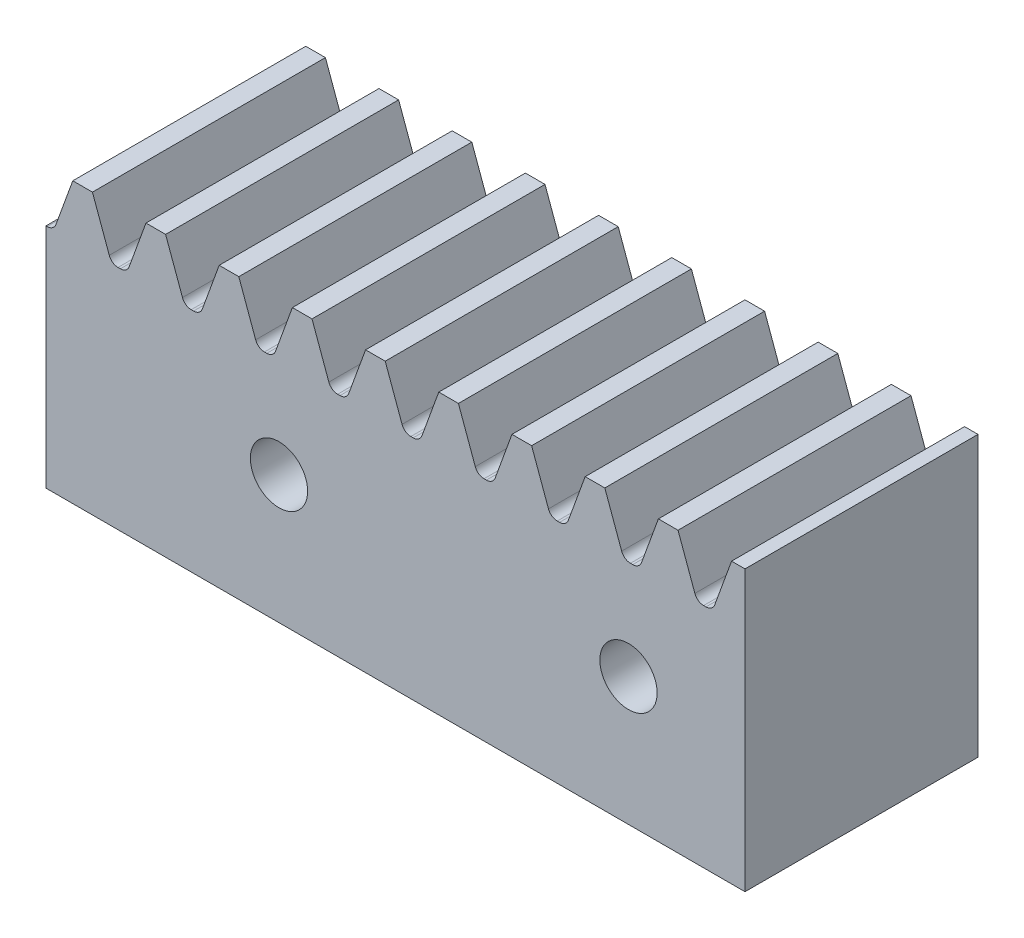
SolidWorks part; units mm, degrees
ref_plane "Front Plane" through (0, 0, 0) normal (0, 0, 1) x (1, 0, 0)
ref_plane "Top Plane" through (0, 0, 0) normal (0, 1, 0) x (1, 0, 0)
ref_plane "Right Plane" through (0, 0, 0) normal (1, 0, 0) x (0, 0, -1)
ref_plane "Dim.Module" through (1, 0, 0) normal (1, 0, 0) x (0, 0, -1)
sketch "Sketch1" plane through (0, 0, 0) normal (0, 0, 1) x (1, 0, 0)
  line L1 (0, 0) -> (30, 0)
  line L2 (0, 0) -> (0, 12)
  line L3 (0, 12) -> (30, 12)
  line L4 (30, 0) -> (30, 12)
  dimension "H" = 12
  dimension "L" = 30
extrude "Boss-Extrude1" add sketch "Sketch1" against normal mid plane 10
sketch "Sketch2" plane through (0, 0, 5) normal (0, 0, 1) x (1, 0, 0)
  line L0 (0, 0) -> (0, 12) construction
  line L2 (-1.1494, 12) -> (1.1494, 12)
  line L3 (1.1494, 12) -> (0.4262, 10.0132)
  line L4 (0.0504, 9.75) -> (-0.0504, 9.75)
  line L5 (30, 0) -> (30, 12) construction
  line L6 (-0.7854, 11) -> (30, 11) construction
  line L9 (-1.1494, 12) -> (-0.4262, 10.0132)
  line L10 (0, 12) -> (0, 0) construction
  line L11 (30, 12) -> (0, 12) construction
  arc A0 (0.4262, 10.0132) -> (0.0504, 9.75) centre (0.0504, 10.15) cw
  arc A1 (-0.4262, 10.0132) -> (-0.0504, 9.75) centre (-0.0504, 10.15) ccw
  dimension "D2" = 20
  dimension "H_s" = 11
  dimension "KSS_3" = 0.4
extrude "Cut-Extrude1" cut sketch "Sketch2" against normal through all
pattern_linear "LPattern1" count 10 spacing 3.1416 along (1, 0, 0) of "Cut-Extrude1"
hole_wizard "Tap1" positions "Sketch4" profile "Sketch3" hole size "M3x0.5" standard "JIS"
sketch "Sketch4" plane through (-45.4166, 4.6308, 5) normal (0, 0, -1) x (-1, 0, 0)
  line L0 (-45.4166, 0.8692) -> (-75.4166, 0.8692) construction
  line L4 (-45.4166, -4.6308) -> (-75.4166, -4.6308) construction
  line L7 (-45.4166, -4.6308) -> (-45.4166, 7.3692) construction
  line L8 (-75.4166, -4.6308) -> (-75.4166, 7.3692) construction
  point P0 (-55.4166, 0.8692)
  dimension "A" = 10
  dimension "H_s/2" = 5.5
sketch "Sketch3" plane through (10, 5.5, 5) normal (1, 0, 0) x (0, -1, 0)
  line L0 (0, 0) -> (0, 6.7388)
  line L1 (0, 6.7388) -> (1.2295, 6)
  line L2 (1.2295, 6) -> (1.2295, 0)
  line L5 (1.2295, 0) -> (0, 0)
  line L10 (0, 6.7388) -> (-1.2295, 6) construction
  line L11 (0, 0) -> (0, 6.7388) construction
  dimension "Drill Angle" = 118
  dimension "HSL_1" = 6
cosmetic thread "Thread1"
hole_wizard "Tap2" [suppressed] positions "Sketch6" profile "Sketch5" hole size "M3x0.5" standard "JIS"
sketch "Sketch6" [suppressed] plane through (-24.5925, 4.8567, 5) normal (0, 0, -1) x (-1, 0, 0)
  line L1 (-174.5925, 0.6433) -> (-24.5925, 0.6433) construction
  line L6 (-24.5925, -4.8567) -> (-24.5925, 7.1433) construction
  line L7 (-174.5925, -4.8567) -> (-174.5925, 7.1433) construction
  line L8 (-24.5925, -4.8567) -> (-174.5925, -4.8567) construction
  point P0 (-69.5925, 0.6433)
  dimension "F" = 0
  dimension "H_s/2" = 5.5
sketch "Sketch5" [suppressed] plane through (45, 5.5, 5) normal (1, 0, 0) x (0, -1, 0)
  line L0 (0, 0) -> (0, 6.7388)
  line L1 (0, 6.7388) -> (1.2295, 6)
  line L2 (1.2295, 6) -> (1.2295, 0)
  line L5 (1.2295, 0) -> (0, 0)
  line L10 (0, 6.7388) -> (-1.2295, 6) construction
  line L11 (0, 0) -> (0, 6.7388) construction
  dimension "Drill Angle" = 118
  dimension "HSL_1" = 6
cosmetic thread "Thread2" [suppressed]
pattern_linear "LPattern2" [suppressed]
hole_wizard "Tap3" positions "Sketch8" profile "Sketch7" hole size "M3x0.5" standard "JIS"
sketch "Sketch8" plane through (-24.7922, 5.7087, 5) normal (0, 0, -1) x (-1, 0, 0)
  line L0 (-24.7922, -0.2087) -> (-54.7922, -0.2087) construction
  line L2 (-24.7922, -5.7087) -> (-24.7922, 6.2913) construction
  line L3 (-24.7922, -5.7087) -> (-54.7922, -5.7087) construction
  line L4 (-54.7922, -5.7087) -> (-54.7922, 6.2913) construction
  point P0 (-49.7922, -0.2087)
  dimension "B" = 15
  dimension "H_s/2" = 5.5
sketch "Sketch7" plane through (25, 5.5, 5) normal (1, 0, 0) x (0, -1, 0)
  line L0 (0, 0) -> (0, 6.7388)
  line L1 (0, 6.7388) -> (1.2295, 6)
  line L2 (1.2295, 6) -> (1.2295, 0)
  line L5 (1.2295, 0) -> (0, 0)
  line L10 (0, 6.7388) -> (-1.2295, 6) construction
  line L11 (0, 0) -> (0, 6.7388) construction
  dimension "Drill Angle" = 118
  dimension "HSL_1" = 6
cosmetic thread "Thread3"
hole_wizard "Tap4" [suppressed] positions "Sketch10" profile "Sketch9" hole size "M3x0.5" standard "JIS"
sketch "Sketch10" [suppressed] plane through (-104.3075, 3.863, 5) normal (0, 0, -1) x (-1, 0, 0)
  line L0 (-104.3075, 1.637) -> (-254.3075, 1.637) construction
  line L3 (-104.3075, -3.863) -> (-104.3075, 8.137) construction
  line L4 (-254.3075, -3.863) -> (-254.3075, 8.137) construction
  line L5 (-104.3075, -3.863) -> (-254.3075, -3.863) construction
  point P0 (-194.3075, 1.637)
  dimension "C" = 30
  dimension "H_s/2" = 5.5
sketch "Sketch9" [suppressed] plane through (90, 5.5, 5) normal (1, 0, 0) x (0, -1, 0)
  line L0 (0, 0) -> (0, 6.7388)
  line L1 (0, 6.7388) -> (1.2295, 6)
  line L2 (1.2295, 6) -> (1.2295, 0)
  line L5 (1.2295, 0) -> (0, 0)
  line L10 (0, 6.7388) -> (-1.2295, 6) construction
  line L11 (0, 0) -> (0, 6.7388) construction
  dimension "Drill Angle" = 118
  dimension "HSL_1" = 6
cosmetic thread "Thread4" [suppressed]
hole_wizard "Tap5" [suppressed] positions "Sketch12" profile "Sketch11" hole size "M3x0.5" standard "JIS"
sketch "Sketch12" [suppressed] plane through (42.8428, 5.5342, 5) normal (0, 0, -1) x (-1, 0, 0)
  line L0 (42.8428, -0.0342) -> (-107.1572, -0.0342) construction
  line L1 (42.8428, -5.5342) -> (42.8428, 6.4658) construction
  line L2 (-107.1572, -5.5342) -> (-107.1572, 6.4658) construction
  line L3 (42.8428, -5.5342) -> (-107.1572, -5.5342) construction
  point P0 (-77.1572, -0.0342)
  dimension "D" = 30
  dimension "H_s/2" = 5.5
sketch "Sketch11" [suppressed] plane through (120, 5.5, 5) normal (1, 0, 0) x (0, -1, 0)
  line L0 (0, 0) -> (0, 6.7388)
  line L1 (0, 6.7388) -> (1.2295, 6)
  line L2 (1.2295, 6) -> (1.2295, 0)
  line L5 (1.2295, 0) -> (0, 0)
  line L10 (0, 6.7388) -> (-1.2295, 6) construction
  line L11 (0, 0) -> (0, 6.7388) construction
  dimension "Drill Angle" = 118
  dimension "HSL_1" = 6
cosmetic thread "Thread5" [suppressed]
hole_wizard "Tap6" [suppressed] positions "Sketch14" profile "Sketch13" hole size "M3x0.5" standard "JIS"
sketch "Sketch14" [suppressed] plane through (0, 0, 0) normal (-1, 0, 0) x (0, 0, 1)
  line L2 (-5, 0) -> (5, 0) construction
  point P0 (0, 5.5)
  dimension "H_s/2" = 5.5
sketch "Sketch13" [suppressed] plane through (0, 5.5, 0) normal (0, 1, 0) x (0, 0, 1)
  line L0 (0, 0) -> (0, 8.2388)
  line L1 (0, 8.2388) -> (1.2295, 7.5)
  line L2 (1.2295, 7.5) -> (1.2295, 0)
  line L5 (1.2295, 0) -> (0, 0)
  line L10 (0, 8.2388) -> (-1.2295, 7.5) construction
  line L11 (0, 0) -> (0, 8.2388) construction
  dimension "Drill Angle" = 118
  dimension "HSL_2" = 7.5
cosmetic thread "Thread6" [suppressed]
hole_wizard "Tap7" [suppressed] positions "Sketch16" profile "Sketch15" hole size "M3x0.5" standard "JIS"
sketch "Sketch16" [suppressed] plane through (0, 0, 0) normal (-1, 0, 0) x (0, 0, 1)
  line L1 (-5, 0) -> (5, 0) construction
  line L6 (0, 0) -> (0, 12) construction
  point P0 (0, 5.5)
  dimension "H_s/2" = 5.5
sketch "Sketch15" [suppressed] plane through (0, 5.5, 0) normal (0, 1, 0) x (0, 0, 1)
  line L0 (0, 0) -> (0, 8.2388)
  line L1 (0, 8.2388) -> (1.2295, 7.5)
  line L2 (1.2295, 7.5) -> (1.2295, 0)
  line L5 (1.2295, 0) -> (0, 0)
  line L10 (0, 8.2388) -> (-1.2295, 7.5) construction
  line L11 (0, 0) -> (0, 8.2388) construction
  dimension "Drill Angle" = 118
  dimension "HSL_3" = 7.5
cosmetic thread "Thread7" [suppressed]
hole_wizard "Tap8" [suppressed] positions "Sketch18" profile "Sketch17" hole size "M3x0.5" standard "JIS"
sketch "Sketch18" [suppressed] plane through (150, -0.0905, -0.628) normal (1, 0, 0) x (0, 0, -1)
  line L1 (-0.628, 0.0905) -> (-0.628, 12.0905) construction
  point P0 (-0.628, 5.5905)
  dimension "H_s/2" = 5.5
sketch "Sketch17" [suppressed] plane through (150, 5.5, 0) normal (0, 1, 0) x (0, 0, -1)
  line L0 (0, 0) -> (0, 8.2388)
  line L1 (0, 8.2388) -> (1.2295, 7.5)
  line L2 (1.2295, 7.5) -> (1.2295, 0)
  line L5 (1.2295, 0) -> (0, 0)
  line L10 (0, 8.2388) -> (-1.2295, 7.5) construction
  line L11 (0, 0) -> (0, 8.2388) construction
  dimension "Drill Angle" = 118
  dimension "HSL_3" = 7.5
cosmetic thread "Thread8" [suppressed]
sketch "Sketch20" [suppressed] plane through (0, 0, 0) normal (0, 0, 1) x (1, 0, 0)
  line L1 (0, 9.75) -> (150, 9.75)
  line L2 (0, 9.75) -> (0, 0)
  line L3 (0, 0) -> (150, 0)
  line L4 (150, 9.75) -> (150, 0)
extrude "Boss-Extrude2" [suppressed] add sketch "Sketch20" along normal mid plane 10
hole_wizard "Tap9" [suppressed] positions "Sketch22" profile "Sketch21" hole size "M4x0.7" standard "JIS"
sketch "Sketch22" [suppressed] plane through (-12.4149, 1.7574, 5) normal (0, 0, 1) x (-1, 0, 0)
  point P0 (-42.4149, -3.7426)
sketch "Sketch21" [suppressed] plane through (30, 5.5, 5) normal (1, 0, 0) x (0, -1, 0)
  line L0 (0, 0) -> (0, 9.074)
  line L1 (0, 9.074) -> (1.621, 8.1)
  line L2 (1.621, 8.1) -> (1.621, 0)
  line L5 (1.621, 0) -> (0, 0)
  line L10 (0, 9.074) -> (-1.621, 8.1) construction
  line L11 (0, 0) -> (0, 9.074) construction
  dimension "Drill Angle" = 118
  dimension "HSL_4" = 8.1
cosmetic thread "Thread9" [suppressed]
hole_wizard "Tap10" [suppressed] positions "Sketch24" profile "Sketch23" hole size "M4x0.7" standard "JIS"
sketch "Sketch24" [suppressed] plane through (-4.0377, 1.955, 5) normal (0, 0, 1) x (-1, 0, 0)
  line L0 (-4.0377, -3.545) -> (-154.0377, -3.545) construction
  point P0 (-64.0377, -3.545)
sketch "Sketch23" [suppressed] plane through (60, 5.5, 5) normal (1, 0, 0) x (0, -1, 0)
  line L0 (0, 0) -> (0, 9.074)
  line L1 (0, 9.074) -> (1.621, 8.1)
  line L2 (1.621, 8.1) -> (1.621, 0)
  line L5 (1.621, 0) -> (0, 0)
  line L10 (0, 9.074) -> (-1.621, 8.1) construction
  line L11 (0, 0) -> (0, 9.074) construction
  dimension "Drill Angle" = 118
  dimension "HSL_4" = 8.1
cosmetic thread "Thread10" [suppressed]
hole_wizard "Tap11" [suppressed] positions "Sketch26" profile "Sketch25" hole size "M4x0.7" standard "JIS"
sketch "Sketch26" [suppressed] plane through (21.3365, 0.9985, 5) normal (0, 0, 1) x (-1, 0, 0)
  point P0 (-68.6635, -4.5015)
sketch "Sketch25" [suppressed] plane through (90, 5.5, 5) normal (1, 0, 0) x (0, -1, 0)
  line L0 (0, 0) -> (0, 9.074)
  line L1 (0, 9.074) -> (1.621, 8.1)
  line L2 (1.621, 8.1) -> (1.621, 0)
  line L5 (1.621, 0) -> (0, 0)
  line L10 (0, 9.074) -> (-1.621, 8.1) construction
  line L11 (0, 0) -> (0, 9.074) construction
  dimension "Drill Angle" = 118
  dimension "HSL_4" = 8.1
cosmetic thread "Thread11" [suppressed]
hole_wizard "Tap12" [suppressed] positions "Sketch28" profile "Sketch27" hole size "M4x0.7" standard "JIS"
sketch "Sketch28" [suppressed] plane through (-47.757, 1.1004, 5) normal (0, 0, 1) x (-1, 0, 0)
  point P0 (-167.757, -4.3996)
sketch "Sketch27" [suppressed] plane through (120, 5.5, 5) normal (1, 0, 0) x (0, -1, 0)
  line L0 (0, 0) -> (0, 9.074)
  line L1 (0, 9.074) -> (1.621, 8.1)
  line L2 (1.621, 8.1) -> (1.621, 0)
  line L5 (1.621, 0) -> (0, 0)
  line L10 (0, 9.074) -> (-1.621, 8.1) construction
  line L11 (0, 0) -> (0, 9.074) construction
  dimension "Drill Angle" = 118
  dimension "HSL_4" = 8.1
cosmetic thread "Thread12" [suppressed]
hole_wizard "Tap13" [suppressed] positions "Sketch30" profile "Sketch29" hole size "M4x0.7" standard "JIS"
sketch "Sketch30" [suppressed] plane through (-21.3318, 4.3034, 5) normal (0, 0, -1) x (-1, 0, 0)
  line L0 (-21.3318, 1.1966) -> (-171.3318, 1.1966) construction
  line L1 (-21.3318, -4.3034) -> (-171.3318, -4.3034) construction
  line L2 (-21.3318, -4.3034) -> (-21.3318, 7.6966) construction
  line L3 (-171.3318, -4.3034) -> (-171.3318, 7.6966) construction
  point P0 (-66.3318, 1.1966)
  dimension "F" = 0
  dimension "H_s/2" = 5.5
sketch "Sketch29" [suppressed] plane through (45, 5.5, 5) normal (1, 0, 0) x (0, -1, 0)
  line L0 (0, 0) -> (0, 9.074)
  line L1 (0, 9.074) -> (1.621, 8.1)
  line L2 (1.621, 8.1) -> (1.621, 0)
  line L5 (1.621, 0) -> (0, 0)
  line L10 (0, 9.074) -> (-1.621, 8.1) construction
  line L11 (0, 0) -> (0, 9.074) construction
  dimension "Drill Angle" = 118
  dimension "HSL_4" = 8.1
cosmetic thread "Thread13" [suppressed]
pattern_linear "LPattern3" [suppressed]
hole_wizard "Tap14" [suppressed] positions "Sketch32" profile "Sketch31" hole size "M4x0.7" standard "JIS"
sketch "Sketch32" [suppressed] plane through (0, 0, 0) normal (-1, 0, 0) x (0, 0, 1)
  point P0 (0, 5.5)
sketch "Sketch31" [suppressed] plane through (0, 5.5, 0) normal (0, 1, 0) x (0, 0, 1)
  line L0 (0, 0) -> (0, 8.2388)
  line L1 (0, 8.2388) -> (1.2295, 7.5)
  line L2 (1.2295, 7.5) -> (1.2295, 0)
  line L5 (1.2295, 0) -> (0, 0)
  line L10 (0, 8.2388) -> (-1.2295, 7.5) construction
  line L11 (0, 0) -> (0, 8.2388) construction
  dimension "Drill Angle" = 118
  dimension "HSL_2" = 7.5
cosmetic thread "Thread14" [suppressed]
hole_wizard "Tap15" [suppressed] positions "Sketch34" profile "Sketch33" hole size "M3x0.5" standard "JIS"
sketch "Sketch34" [suppressed] plane through (0, 0, 0) normal (-1, 0, 0) x (0, 0, 1)
  line L0 (0, 0) -> (0, 12) construction
  point P0 (0, 5.5)
sketch "Sketch33" [suppressed] plane through (0, 5.5, 0) normal (0, 1, 0) x (0, 0, 1)
  line L0 (0, 0) -> (0, 8.2388)
  line L1 (0, 8.2388) -> (1.2295, 7.5)
  line L2 (1.2295, 7.5) -> (1.2295, 0)
  line L5 (1.2295, 0) -> (0, 0)
  line L10 (0, 8.2388) -> (-1.2295, 7.5) construction
  line L11 (0, 0) -> (0, 8.2388) construction
  dimension "Drill Angle" = 118
  dimension "HSL_3" = 7.5
cosmetic thread "Thread15" [suppressed]
hole_wizard "Tap16" [suppressed] positions "Sketch36" profile "Sketch35" hole size "M3x0.5" standard "JIS"
sketch "Sketch36" [suppressed] plane through (150, 0, 0) normal (1, 0, 0) x (0, 0, -1)
  line L0 (0, 0) -> (0, 12) construction
  point P0 (0, 5.5)
sketch "Sketch35" [suppressed] plane through (150, 5.5, 0) normal (0, 1, 0) x (0, 0, -1)
  line L0 (0, 0) -> (0, 8.2388)
  line L1 (0, 8.2388) -> (1.2295, 7.5)
  line L2 (1.2295, 7.5) -> (1.2295, 0)
  line L5 (1.2295, 0) -> (0, 0)
  line L10 (0, 8.2388) -> (-1.2295, 7.5) construction
  line L11 (0, 0) -> (0, 8.2388) construction
  dimension "Drill Angle" = 118
  dimension "HSL_3" = 7.5
cosmetic thread "Thread16" [suppressed]
ref_plane "Dim.M" through (3, 0, 0) normal (1, 0, 0) x (0, 0, -1)
ref_plane "Dim.MC" through (3, 0, 0) normal (1, 0, 0) x (0, 0, -1)
ref_plane "Dim.WMC" through (3, 0, 0) normal (1, 0, 0) x (0, 0, -1)
ref_plane "Dim.TPC" through (4, 0, 0) normal (1, 0, 0) x (0, 0, -1)
equation "\"H_s/2\"= \"H_s\" / 2"
equation "\"F\"= ( \"L\" - \"B\" * ( \"K\" - 1 ) ) / 2"
equation "\"KSS_1\"= INT ( ( \"L\" / ( \"Module\" * PI ) ) ) + 2"
equation "\"P\"= \"Module\" * PI"
equation "\"KSS_2\"= 1.25 * \"Module\""
equation "\"KSS_3\"= 0.4 * \"Module\""
equation "\"KSS_4\"= ( \"Module\" * PI ) / 2"
equation "\"Factor\"= 1.082532"
equation "\"Pitch_M\"= IIF ( \"M\" = 30 , 3.5 , IIF ( \"M\" = 27 , 3 , IIF ( \"M\" = 24 , 3 , IIF ( \"M\" = 22 , 2.5 , IIF ( \"M\" = 20 , 2.5 , IIF ( \"M\" = 18 , 2.5 , IIF ( \"M\" = 16 , 2 , IIF ( \"M\" = 12 , 1.75 , IIF ( \"M\" = 10 , 1.5 , IIF ( \"M\" = 8 , 1.25 , IIF ( \"M\" = 6 , 1 , IIF ( \"M\" = 5 , 0.8 , IIF ( \"M\" = 4 , 0.7 , IIF ( \"M\" = 3.5 , 0.6 , IIF ( \"M\" = 3 , 0.5 , IIF ( \"M\" = 2.6 , 0.45 , 0.4 ) ) ) ) ) ) ) ) ) ) ) ) ) ) ) )"
equation "\"HSD_1\"= round ( \"M\" - \"Factor\" * \"Pitch_M\" , 3 )"
equation "\"Mx1.5\"= \"M\" * 1.5"
equation "\"HSL_1\"= round ( \"Mx1.5\" + \"Pitch_M\" * 3 , 1 )"
equation "\"Pitch_MC\"= IIF ( \"MC\" = 30 , 3.5 , IIF ( \"MC\" = 27 , 3 , IIF ( \"MC\" = 24 , 3 , IIF ( \"MC\" = 22 , 2.5 , IIF ( \"MC\" = 20 , 2.5 , IIF ( \"MC\" = 18 , 2.5 , IIF ( \"MC\" = 16 , 2 , IIF ( \"MC\" = 12 , 1.75 , IIF ( \"MC\" = 10 , 1.5 , IIF ( \"MC\" = 8 , 1.25 , IIF ( \"MC\" = 6 , 1 , IIF ( \"MC\" = 5 , 0.8 , IIF ( \"MC\" = 4 , 0.7 , IIF ( \"MC\" = 3.5 , 0.6 , IIF ( \"MC\" = 3 , 0.5 , IIF ( \"MC\" = 2.6 , 0.45 , 0.4 ) ) ) ) ) ) ) ) ) ) ) ) ) ) ) )"
equation "\"MCx2\"= \"MC\" * 2"
equation "\"HSD_2\"= round ( \"MC\" - \"Factor\" * \"Pitch_MC\" , 3 )"
equation "\"HSL_2\"= round ( \"MCx2\" + \"Pitch_MC\" * 3 , 1 )"
equation "\"Pitch_WMC\"= IIF ( \"WMC\" = 30 , 3.5 , IIF ( \"WMC\" = 27 , 3 , IIF ( \"WMC\" = 24 , 3 , IIF ( \"WMC\" = 22 , 2.5 , IIF ( \"WMC\" = 20 , 2.5 , IIF ( \"WMC\" = 18 , 2.5 , IIF ( \"WMC\" = 16 , 2 , IIF ( \"WMC\" = 12 , 1.75 , IIF ( \"WMC\" = 10 , 1.5 , IIF ( \"WMC\" = 8 , 1.25 , IIF ( \"WMC\" = 6 , 1 , IIF ( \"WMC\" = 5 , 0.8 , IIF ( \"WMC\" = 4 , 0.7 , IIF ( \"WMC\" = 3.5 , 0.6 , IIF ( \"WMC\" = 3 , 0.5 , IIF ( \"WMC\" = 2.6 , 0.45 , 0.4 ) ) ) ) ) ) ) ) ) ) ) ) ) ) ) )"
equation "\"WMCx2\"= \"WMC\" * 2"
equation "\"HSD_3\"= round ( \"WMC\" - \"Factor\" * \"Pitch_WMC\" , 3 )"
equation "\"HSL_3\"= round ( \"WMCx2\" + \"Pitch_WMC\" * 3 , 1 )"
equation "\"Pitch_TPC\"= IIF ( \"TPC\" = 30 , 3.5 , IIF ( \"TPC\" = 27 , 3 , IIF ( \"TPC\" = 24 , 3 , IIF ( \"TPC\" = 22 , 2.5 , IIF ( \"TPC\" = 20 , 2.5 , IIF ( \"TPC\" = 18 , 2.5 , IIF ( \"TPC\" = 16 , 2 , IIF ( \"TPC\" = 12 , 1.75 , IIF ( \"TPC\" = 10 , 1.5 , IIF ( \"TPC\" = 8 , 1.25 , IIF ( \"TPC\" = 6 , 1 , IIF ( \"TPC\" = 5 , 0.8 , IIF ( \"TPC\" = 4 , 0.7 , IIF ( \"TPC\" = 3.5 , 0.6 , IIF ( \"TPC\" = 3 , 0.5 , IIF ( \"TPC\" = 2.6 , 0.45 , 0.4 ) ) ) ) ) ) ) ) ) ) ) ) ) ) ) )"
equation "\"TPCx1.5\"= \"TPC\" * 1.5"
equation "\"HSD_4\"= round ( \"TPC\" - \"Factor\" * \"Pitch_TPC\" , 3 )"
equation "\"HSL_4\"= round ( \"TPCx1.5\" + \"Pitch_TPC\" * 3 , 1 )"
